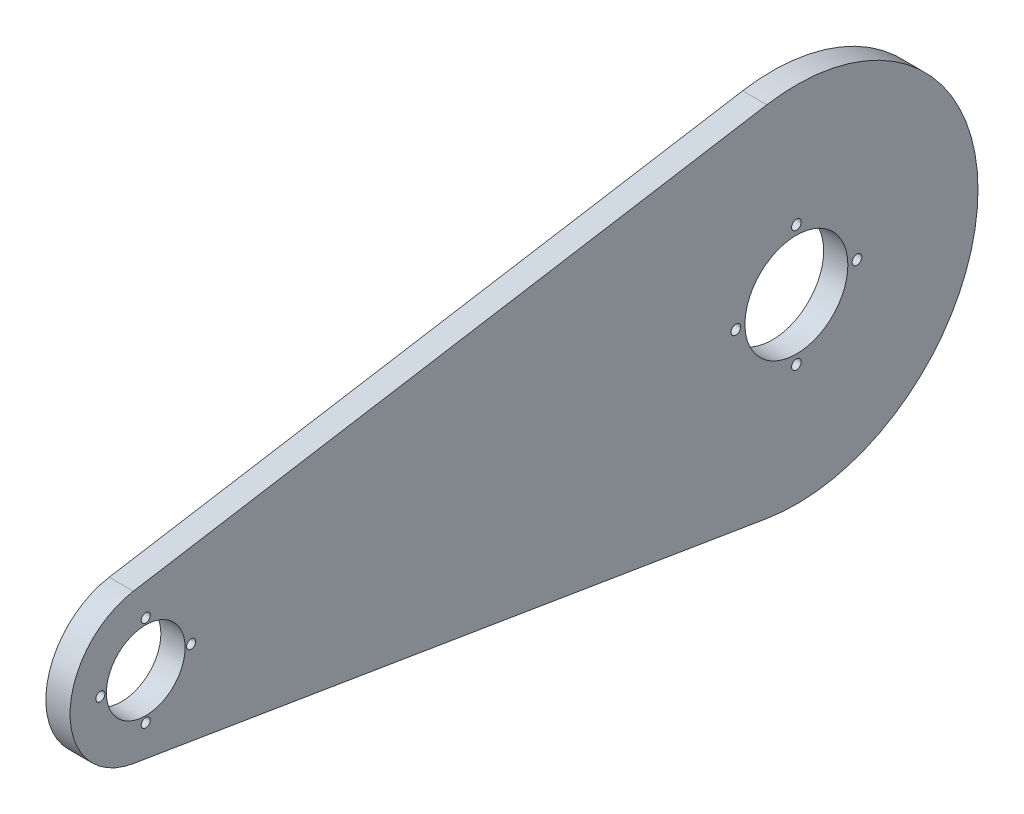
SolidWorks part; units mm, degrees
ref_plane "Front Plane" through (0, 0, 0) normal (0, 0, 1) x (1, 0, 0)
ref_plane "Top Plane" through (0, 0, 0) normal (0, 1, 0) x (1, 0, 0)
ref_plane "Right Plane" through (0, 0, 0) normal (1, 0, 0) x (0, 0, -1)
sketch "Sketch1" plane through (0, 0, 0) normal (1, 0, 0) x (0, 0, -1)
  line L0 (0, 0) -> (-215, 0) construction
  line L1 (-219.0698, 24.6665) -> (-9.7674, 59.1996)
  line L2 (-219.0698, -24.6665) -> (-9.7674, -59.1996)
  circle A0 centre (0, 0) radius 17
  arc A1 (-9.7674, -59.1996) -> (-9.7674, 59.1996) centre (0, 0) ccw
  arc A2 (-219.0698, 24.6665) -> (-219.0698, -24.6665) centre (-215, 0) ccw
  circle A3 centre (-215, 0) radius 13
  dimension "D1" = 120
  dimension "D2" = 34
  dimension "D3" = 25
  dimension "D4" = 26
  dimension "D5" = 215
extrude "Boss-Extrude1" add sketch "Sketch1" along normal mid plane 8
sketch "Sketch2" plane through (4, 0, 0) normal (1, 0, 0) x (0, 0, -1)
  line L0 (0, 0) -> (0, 20) construction
  circle A0 centre (0, 20) radius 1.6
  circle A1 centre (20, 0) radius 1.6
  circle A2 centre (0, -20) radius 1.6
  circle A3 centre (-20, 0) radius 1.6
  circle A4 centre (-215, 0) radius 15 construction
  circle A5 centre (-215, 15) radius 1.5
  circle A6 centre (-200, 0) radius 1.5
  circle A7 centre (-215, -15) radius 1.5
  circle A8 centre (-230, 0) radius 1.5
  point P13 (0, 0)
  point P25 (-215, 0)
  dimension "D1" = 3.2
  dimension "D6" = 30
  dimension "D7" = 3
  dimension "D2" = 20
  dimension "D4" = 20
  dimension "D5" = 20
  dimension "D3" = 4
  dimension "D8" = 4
extrude "Cut-Extrude1" cut sketch "Sketch2" against normal through all
equation "\"D4@Sketch2\"=\"D2@Sketch2\""
equation "\"D5@Sketch2\"=\"D2@Sketch2\""
equation "\"shaft-diameter\" =20mm"
equation "\"key-length\"=12mm"
equation "\"key-width\"=4mm"
equation "\"flippershaft-wormgear-diameter\" = 35mm"
equation "\"shaft-ring-groove-depth\"=0.5mm"
equation "\"shaft-ring-groove-width\" = 1.3mm"
equation "\"mini-shaft-diameter\" = 12mm"
equation "\"mini-flipper-shaft-diameter\"= 26mm"
equation "\"D4@Sketch1\"=\"mini-flipper-shaft-diameter\""
